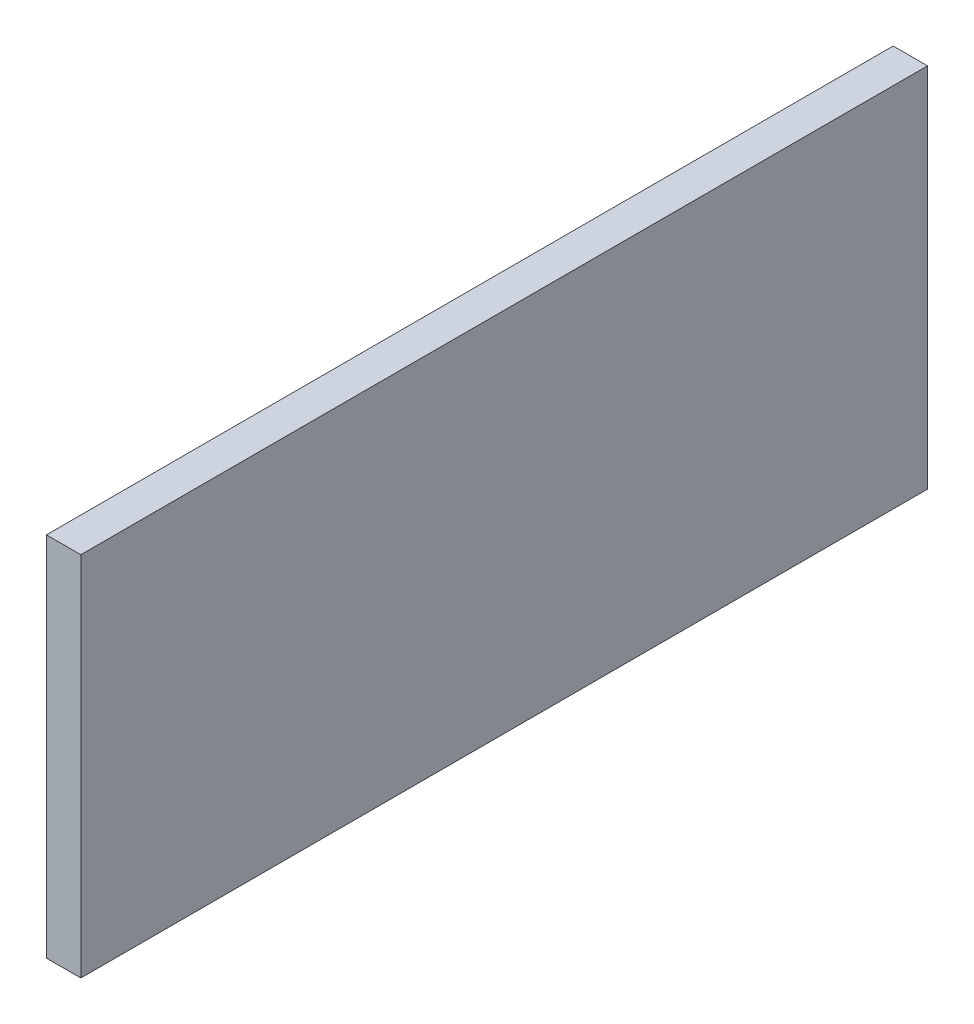
SolidWorks part; units mm, degrees
material "Balsa"
ref_plane "Front Plane" through (0, 0, 0) normal (0, 0, 1) x (1, 0, 0)
ref_plane "Top Plane" through (0, 0, 0) normal (0, 1, 0) x (1, 0, 0)
ref_plane "Right Plane" through (0, 0, 0) normal (1, 0, 0) x (0, 0, -1)
sketch "Sketch2" plane through (0, 0, 0) normal (1, 0, 0) x (0, 0, -1)
  line L0 (0, 0) -> (0, 50.8)
  line L1 (0, 50.8) -> (117.348, 50.8)
  line L2 (117.348, 50.8) -> (117.348, 0)
  line L3 (117.348, 0) -> (0, 0)
  dimension "D1" = 117.348
  dimension "D2" = 50.8
extrude "Boss-Extrude1" add sketch "Sketch2" along normal blind 4.7625
